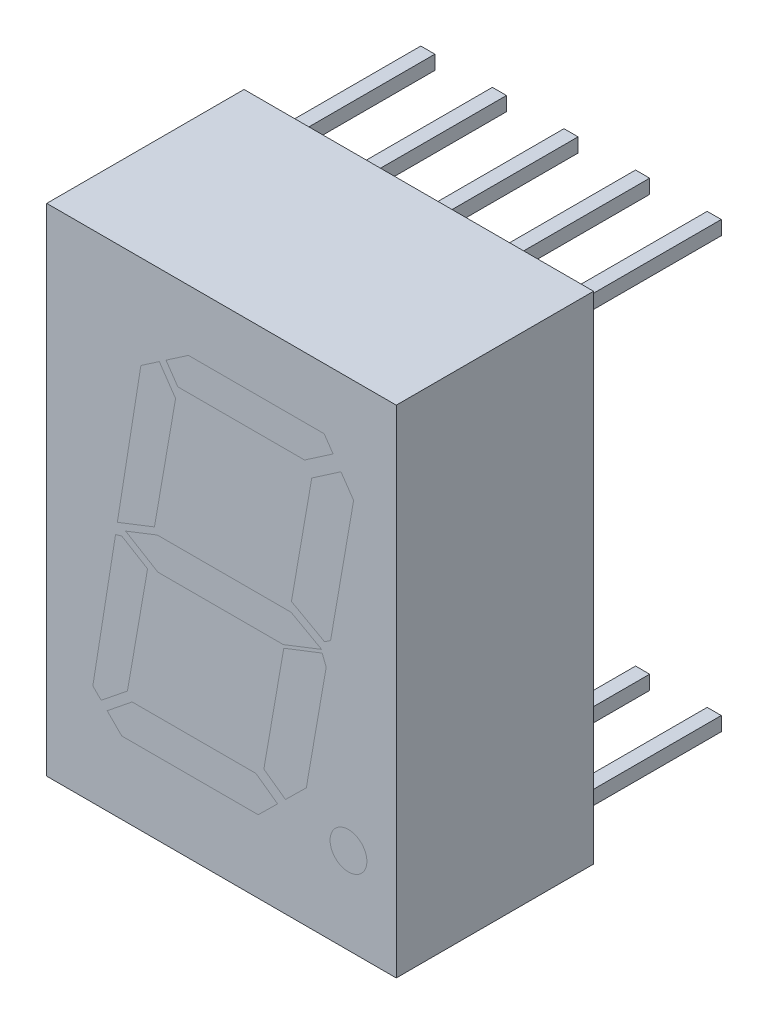
SolidWorks part; units mm, degrees
ref_plane "Plan de face" through (0, 0, 0) normal (0, 0, 1) x (1, 0, 0)
ref_plane "Plan de dessus" through (0, 0, 0) normal (0, 1, 0) x (1, 0, 0)
ref_plane "Plan de droite" through (0, 0, 0) normal (1, 0, 0) x (0, 0, -1)
sketch "Esquisse1" plane through (0, 0, 0) normal (0, 0, 1) x (1, 0, 0)
  line L1 (0, 0) -> (12.4, 0)
  line L2 (0, 0) -> (0, 17.6)
  line L3 (0, 17.6) -> (12.4, 17.6)
  line L4 (12.4, 0) -> (12.4, 17.6)
  dimension "D1" = 17.6
  dimension "D2" = 12.4
extrude "Boss.-Extru.1" add sketch "Esquisse1" along normal blind 7
sketch "Esquisse2" plane through (0, 0, 0) normal (0, 0, -1) x (-1, 0, 0)
  line L0 (-6.2, 17.6) -> (-6.2, 0) construction
  line L1 (-12.4, 17.6) -> (0, 17.6) construction
  line L2 (0, 0) -> (-12.4, 0) construction
  line L3 (-12.4, 8.8) -> (0, 8.8) construction
  line L4 (-12.4, 0) -> (-12.4, 17.6) construction
  line L5 (0, 17.6) -> (0, 0) construction
  line L6 (-6.45, 16.67) -> (-5.95, 16.17) construction
  line L7 (-6.45, 1.43) -> (-5.95, 1.43)
  line L8 (-6.45, 1.43) -> (-6.45, 0.93)
  line L9 (-6.45, 0.93) -> (-5.95, 0.93)
  line L10 (-5.95, 1.43) -> (-5.95, 0.93)
  line L11 (-6.45, 1.43) -> (-5.95, 0.93) construction
  line L12 (-6.45, 0.93) -> (-5.95, 1.43) construction
  line L13 (-6.45, 16.17) -> (-5.95, 16.67) construction
  line L14 (-5.95, 16.17) -> (-5.95, 16.67)
  line L15 (-6.45, 16.67) -> (-5.95, 16.67)
  line L16 (-6.45, 16.17) -> (-6.45, 16.67)
  line L17 (-6.45, 16.17) -> (-5.95, 16.17)
  point P12 (-6.2, 1.18)
  point P21 (-6.2, 16.42)
  dimension "D1" = 15.24
  dimension "D2" = 0.5
  dimension "D3" = 0.5
extrude "Boss.-Extru.2" add sketch "Esquisse2" along normal blind 5.4
pattern_linear "Répétition linéaire1" count 3 spacing 2.54 along (1, 0, 0) count 3 spacing 2.54 along (-1, 0, 0) of "Boss.-Extru.2"
sketch "Esquisse3"
sketch "Esquisse4" plane through (0, 0, 7) normal (0, 0, 1) x (1, 0, 0)
  line L0 (1.6357, 3.5923) -> (1.9303, 3.2978)
  line L1 (1.9303, 3.2978) -> (2.8636, 4.0496)
  line L2 (2.8636, 4.0496) -> (3.5765, 8.1587)
  line L3 (3.5765, 8.1587) -> (2.6606, 8.7108)
  line L4 (2.6606, 8.7108) -> (2.4405, 8.645)
  line L5 (2.4405, 8.645) -> (1.6357, 3.5923)
  line L6 (3.0294, 3.7967) -> (7.4216, 3.7967)
  line L7 (7.4216, 3.7967) -> (8.1905, 3.2451)
  line L8 (8.1905, 3.2451) -> (7.5013, 2.5673)
  line L9 (7.5013, 2.5673) -> (2.6608, 2.5673)
  line L10 (2.6608, 2.5673) -> (2.1443, 3.0837)
  line L11 (2.1443, 3.0837) -> (3.0294, 3.7967)
  line L12 (7.703, 4.0697) -> (8.4085, 8.136)
  line L13 (8.4085, 8.136) -> (9.771, 8.669)
  line L14 (9.771, 8.669) -> (9.9135, 8.3048)
  line L15 (9.9135, 8.3048) -> (9.2095, 4.2473)
  line L16 (9.2095, 4.2473) -> (8.4697, 3.5196)
  line L17 (8.4697, 3.5196) -> (7.703, 4.0697)
  line L18 (2.5056, 9.0543) -> (3.8212, 9.5689)
  line L19 (3.8212, 9.5689) -> (4.5711, 13.891)
  line L20 (4.5711, 13.891) -> (3.993, 14.7356)
  line L21 (3.993, 14.7356) -> (3.3393, 14.2882)
  line L22 (3.3393, 14.2882) -> (2.5056, 9.0543)
  line L23 (4.2321, 14.8993) -> (5.0267, 15.4431)
  line L24 (5.0267, 15.4431) -> (9.843, 15.4431)
  line L25 (9.843, 15.4431) -> (10.1595, 14.9806)
  line L26 (10.1595, 14.9806) -> (9.1478, 14.2882)
  line L27 (9.1478, 14.2882) -> (4.6503, 14.2882)
  line L28 (4.6503, 14.2882) -> (4.2321, 14.8993)
  line L29 (10.4386, 14.5727) -> (9.4022, 13.8634)
  line L30 (9.4022, 13.8634) -> (8.6815, 9.7093)
  line L31 (8.6815, 9.7093) -> (9.8559, 9.0597)
  line L32 (9.8559, 9.0597) -> (10.069, 9.2012)
  line L33 (10.069, 9.2012) -> (10.8873, 13.9171)
  line L34 (10.8873, 13.9171) -> (10.4386, 14.5727)
  line L35 (2.7973, 8.9308) -> (3.9243, 9.3716)
  line L36 (3.9243, 9.3716) -> (8.6683, 9.3716)
  line L37 (8.6683, 9.3716) -> (9.7528, 8.7718)
  line L38 (9.7528, 8.7718) -> (8.3942, 8.2404)
  line L39 (8.3942, 8.2404) -> (3.9426, 8.2404)
  line L40 (3.9426, 8.2404) -> (2.7973, 8.9308)
  circle A0 centre (10.7048, 3.062) radius 0.653
split line "Ligne de séparation1"
